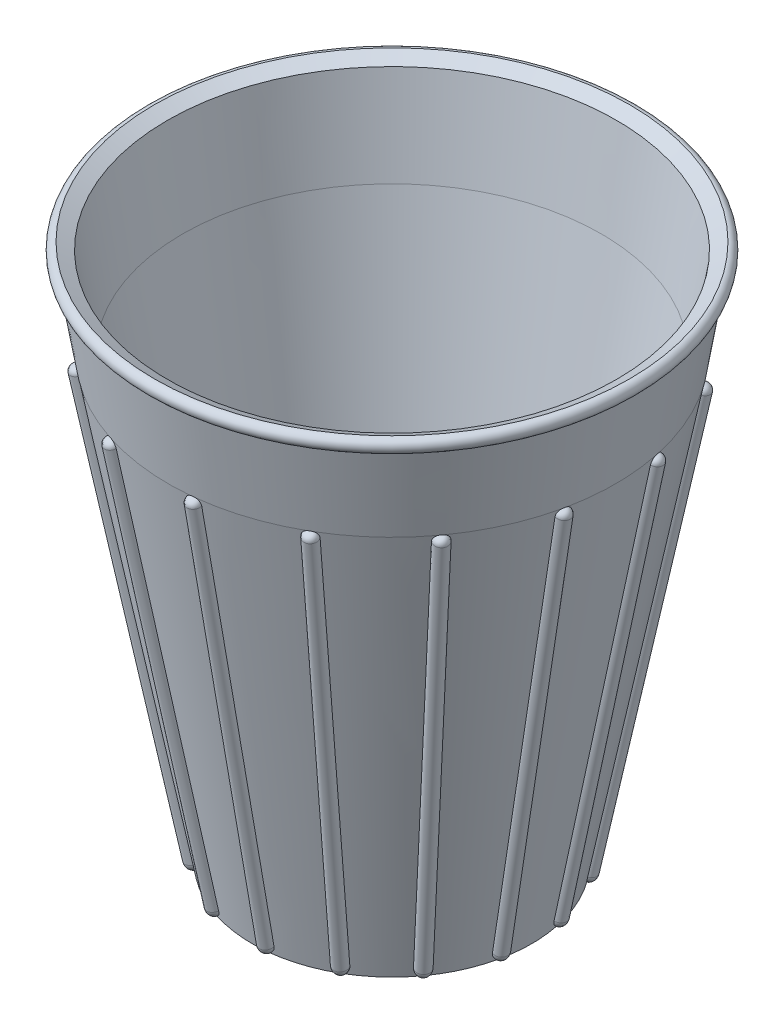
SolidWorks part; units mm, degrees
ref_plane "Front Plane" through (0, 0, 0) normal (0, 0, 1) x (1, 0, 0)
ref_plane "Top Plane" through (0, 0, 0) normal (0, 1, 0) x (1, 0, 0)
ref_plane "Right Plane" through (0, 0, 0) normal (1, 0, 0) x (0, 0, -1)
sketch "Sketch1" plane through (0, 0, 0) normal (0, 0, 1) x (1, 0, 0)
  line L0 (0, 0) -> (0, -77) construction
  line L1 (-20, -77) -> (20, -77) construction
  line L2 (-34, 0) -> (34, 0) construction
  line L3 (-32.1307, -1) -> (-34, 0)
  line L6 (21.5561, -64) -> (20, -77) construction
  line L9 (-34, -2) -> (34, -2) construction
  line L10 (-35, -1) -> (35, -1) construction
  line L11 (-32, -14) -> (32, -14) construction
  line L12 (-34, -2) -> (-32, -14)
  line L15 (34, -2) -> (32, -14) construction
  line L16 (32, -14) -> (27.5, -50.547) construction
  line L17 (27.5, -50.547) -> (23.9354, -64) construction
  line L19 (21.5561, -64) -> (23.9354, -64) construction
  line L22 (0, -74) -> (-18.5355, -74)
  line L27 (-29.964, -14) -> (-32.1307, -1)
  line L28 (-29.964, -14) -> (-18.5355, -74)
  line L29 (-20, -77) -> (-12.6, -77)
  line L30 (-12.6, -77) -> (-12.6, -75.97)
  line L31 (-12.6, -75.97) -> (0, -75.97)
  line L32 (0, -75.97) -> (0, -74)
  line L33 (-32, -14) -> (-20, -77)
  arc A0 (-34, -2) -> (-34, 0) centre (-34, -1) cw
  arc A1 (34, -2) -> (34, 0) centre (34, -1) ccw construction
  point P6 (0, -77)
  point P11 (0, 0)
  point P22 (0, -2)
  point P25 (0, -1)
  point P28 (0, -14)
  dimension "D1" = 77
  dimension "D2" = 40
  dimension "D3" = 68
  dimension "D5" = 2
  dimension "D9" = 2
  dimension "D10" = 68
  dimension "D11" = 70
  dimension "D12" = 1
  dimension "D13" = 14
  dimension "D14" = 64
  dimension "D15" = 1.03
  dimension "D20" = 12.6
  dimension "D21" = 3
revolve "Revolve1" add sketch "Sketch1" angle 360 about L0
sketch "Sketch2" plane through (0, 0, 0) normal (0, 0, 1) x (1, 0, 0)
  line L1 (-32, -14) -> (-20, -77)
  line L4 (-32.9713, -8.9005) -> (9322.6341, -49125.8288) construction
  line L5 (-19.1725, -76) -> (-30.7915, -15) construction
  line L6 (-32, -14) -> (-20, -77) construction
  line L7 (-21.2085, -76) -> (-32.8275, -15)
  line L8 (-32, -14) -> (32, -14) construction
  line L11 (-20, -77) -> (-32, -14)
  line L12 (-20, -77) -> (20, -77) construction
  arc A3 (-32.8275, -15) -> (-32, -14) centre (-32, -14.8424) cw
  arc A4 (-21.2085, -76) -> (-20, -77) centre (-20, -75.7698) ccw
  dimension "D3" = 1
  dimension "D1" = 1
  dimension "D4" = 2
  dimension "D5" = 1
  dimension "D6" = 1
  dimension "D7" = 1
revolve "Revolve7" add sketch "Sketch2" angle 360 about L4
pattern_circular "CirPattern1" count 15 over 360 about axis through (0, -14, 0) along (0, 1, 0) of "Revolve7"
